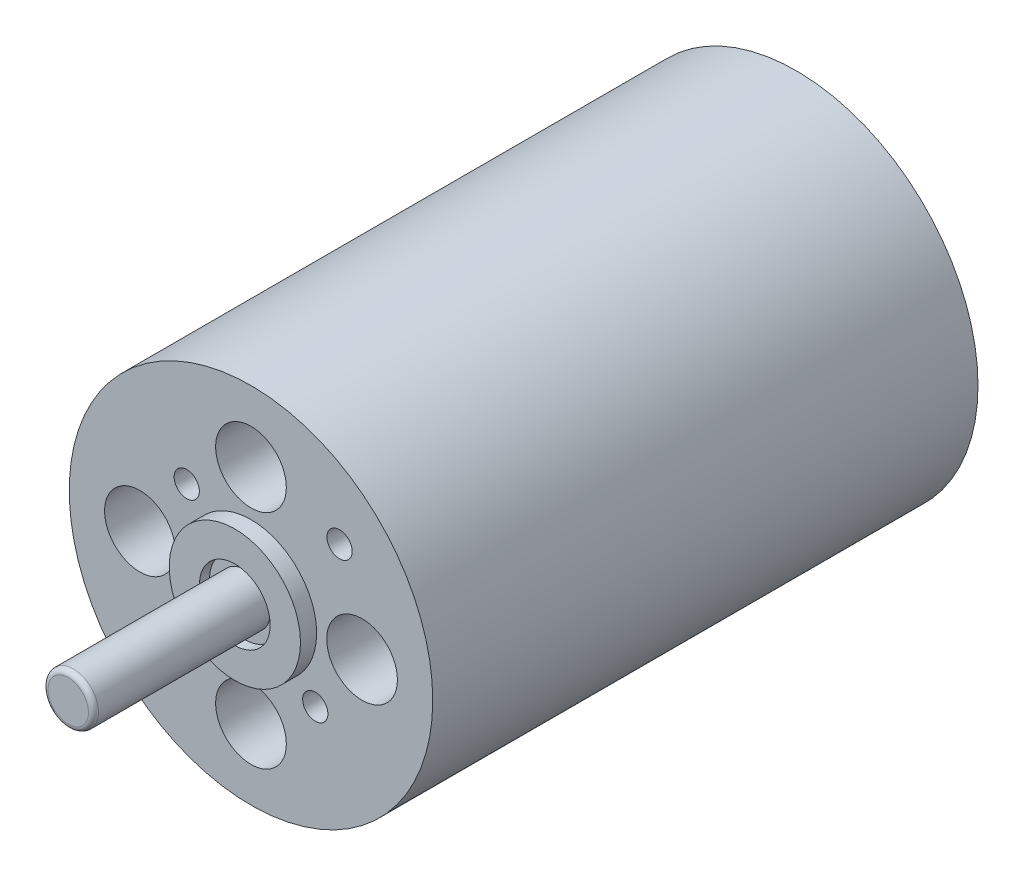
SolidWorks part; units mm, degrees
ref_plane "Plano frontal" through (0, 0, 0) normal (0, 0, 1) x (1, 0, 0)
ref_plane "Plano superior" through (0, 0, 0) normal (0, 1, 0) x (1, 0, 0)
ref_plane "Plano direito" through (0, 0, 0) normal (1, 0, 0) x (0, 0, -1)
sketch "Esboço1" plane through (0, 0, 0) normal (0, 0, 1) x (1, 0, 0)
  circle A0 centre (0, 0) radius 18
  dimension "D1" = 36
extrude "Ressalto-extrusão1" add sketch "Esboço1" along normal mid plane 54
sketch "Esboço2" plane through (0, 0, 0) normal (0, 0, 1) x (1, 0, 0)
  line L0 (6.8426, 6.8426) -> (-22.1779, -22.1779) construction
  line L1 (0, -14.2159) -> (0, 22.9753) construction
  line L2 (21.0585, -21.0585) -> (-5.1058, 5.1058) construction
  circle A0 centre (0, 0) radius 18
  circle A1 centre (0, 0) radius 6.5
  circle A2 centre (-11, 0) radius 3.5
  circle A3 centre (11, 0) radius 3.5
  circle A4 centre (0, -11) radius 3.5
  circle A5 centre (0, 11) radius 3.5
  circle A6 centre (6.364, -6.364) radius 1.25
  circle A7 centre (-6.364, 6.364) radius 1.25
  circle A8 centre (-8.7681, -8.7681) radius 1.25
  circle A9 centre (8.7681, 8.7681) radius 1.25
  point P3 (0, -18)
  point P4 (0, 18)
  point P5 (0, 0)
  point P9 (0, 0)
  dimension "D1" = 36
  dimension "D2" = 13
  dimension "D3" = 7
  dimension "D6" = 7
  dimension "D7" = 7
  dimension "D11" = 2.5
  dimension "D14" = 2.5
  dimension "D4" = 21.095
  dimension "D5" = 11
  dimension "D8" = 11
  dimension "D9" = 11
  dimension "D10" = 9
  dimension "D12" = 13.2626
  dimension "D13" = 13.2626
  dimension "D15" = 12.4
  dimension "D16" = 12.7321
sketch "Esboço7" plane through (0, 0, -27) normal (0, 0, -1) x (-1, 0, 0)
  line L1 (0, -200014.2159) -> (0, 200022.9753) construction
  circle A0 centre (0, 0) radius 3.5
  circle A1 centre (0, 11.5) radius 3
  circle A2 centre (-8.1317, 8.1317) radius 3
  circle A3 centre (-11.5, 0) radius 3
  circle A4 centre (-8.1317, -8.1317) radius 3
  circle A5 centre (0, -11.5) radius 3 [skipped]
  circle A6 centre (8.1317, -8.1317) radius 3
  circle A7 centre (11.5, 0) radius 3
  circle A8 centre (8.1317, 8.1317) radius 3
  point P24 (0, 0)
  dimension "D1" = 7
  dimension "D3" = 6
  dimension "D5" = 12.787
  dimension "D2" = 11.5
  dimension "D6" = 11.5
  dimension "D4" = 8
extrude "Corte-extrusão3" cut sketch "Esboço7" against normal blind 5
sketch "Esboço13" plane through (0, 0, 27) normal (0, 0, 1) x (1, 0, 0)
  circle A0 centre (-11, 0) radius 3.5
  circle A1 centre (11, 0) radius 3.5
  circle A2 centre (0, 11) radius 3.5
  circle A3 centre (0, -11) radius 3.5
  circle A4 centre (-8.7681, -8.7681) radius 1.25
  circle A5 centre (6.364, -6.364) radius 1.25
  circle A6 centre (-6.364, 6.364) radius 1.25
  circle A7 centre (8.7681, 8.7681) radius 1.25
  dimension "D1" = 7
  dimension "D2" = 7
  dimension "D3" = 7
  dimension "D4" = 7
  dimension "D5" = 2.5
  dimension "D6" = 2.5
  dimension "D7" = 2.5
  dimension "D8" = 2.5
extrude "Corte-extrusão4" cut sketch "Esboço13" against normal blind 5
sketch "Esboço14" plane through (0, 0, 27) normal (0, 0, 1) x (1, 0, 0)
  circle A0 centre (0, 0) radius 6.5
  dimension "D1" = 13
extrude "Ressalto-extrusão2" add sketch "Esboço14" along normal blind 1.6
sketch "Esboço17" plane through (0, 0, -27) normal (0, 0, -1) x (-1, 0, 0)
  line L1 (-3.028, -12.4984) -> (3.028, -12.4984) construction
  line L2 (2.5924, -10.7004) -> (3.4636, -14.2963) construction
  arc A0 (-3.028, -12.4984) -> (3.028, -12.4984) centre (0, 0) ccw construction
  arc A1 (-3.4636, -14.2963) -> (3.4636, -14.2963) centre (0, 0) ccw
  arc A2 (-2.5924, -10.7004) -> (2.5924, -10.7004) centre (0, 0) ccw
  arc A3 (-2.5924, -10.7004) -> (-3.4636, -14.2963) centre (-3.028, -12.4984) ccw
  arc A4 (3.4636, -14.2963) -> (2.5924, -10.7004) centre (3.028, -12.4984) ccw
  point P3 (0, -12.8599)
  dimension "D1" = 1.85
  dimension "D2" = 14.7099
  dimension "D3" = 6.056
extrude "Ressalto-extrusão4" add sketch "Esboço17" along normal blind 7
sketch "Esboço18" plane through (0, 0, -34) normal (0, 0, -1) x (-1, 0, 0)
  arc A3 (-3.3929, -14.0048) -> (3.3929, -14.0048) centre (0, 0) ccw
  arc A4 (-3.3929, -14.0048) -> (3.3929, -14.0048) centre (0, 0) ccw
  arc A6 (-2.663, -10.9919) -> (-3.3929, -14.0048) centre (-3.028, -12.4984) ccw
  arc A7 (-2.663, -10.9919) -> (-3.3929, -14.0048) centre (-3.028, -12.4984) ccw
  arc A9 (3.3929, -14.0048) -> (2.663, -10.9919) centre (3.028, -12.4984) ccw
  arc A10 (3.3929, -14.0048) -> (2.663, -10.9919) centre (3.028, -12.4984) ccw
  arc A12 (-2.663, -10.9919) -> (2.663, -10.9919) centre (0, 0) ccw
  arc A13 (-2.663, -10.9919) -> (2.663, -10.9919) centre (0, 0) ccw
  dimension "D1" = 0.3
  dimension "D2" = 0.3
  dimension "D3" = 0.3
  dimension "D4" = 0.3
extrude "Corte-extrusão5" cut sketch "Esboço18" against normal blind 7
sketch "Esboço21" plane through (0, 0, -27) normal (0, 0, -1) x (-1, 0, 0)
  circle A0 centre (-3.028, -12.4984) radius 1.25
  circle A1 centre (3.028, -12.4984) radius 1.25
  circle A8 centre (0, -12.8599) radius 1.25
  arc A9 (-2.663, -10.9919) -> (2.663, -10.9919) centre (0, 0) ccw construction
  point P9 (0, -11.3099)
  dimension "D1" = 2.5
  dimension "D2" = 2.5
  dimension "D3" = 2.5
  dimension "D4" = 1.55
  dimension "D5" = 3.028
extrude "Ressalto-extrusão5" add sketch "Esboço21" along normal blind 7
sketch "Esboço22" plane through (0, 0, 28.6) normal (0, 0, 1) x (1, 0, 0)
  circle A0 centre (0, 0) radius 3.5
  dimension "D1" = 7
extrude "Corte-extrusão6" cut sketch "Esboço22" against normal blind 1
sketch "Esboço23" plane through (0, 0, 27.6) normal (0, 0, 1) x (1, 0, 0)
  circle A0 centre (0, 0) radius 2.5
  dimension "D1" = 5
extrude "Ressalto-extrusão6" add sketch "Esboço23" along normal blind 17.5
fillet "Filete2" radius 0.5 1 edges at (2.5, 0, 45.1)
